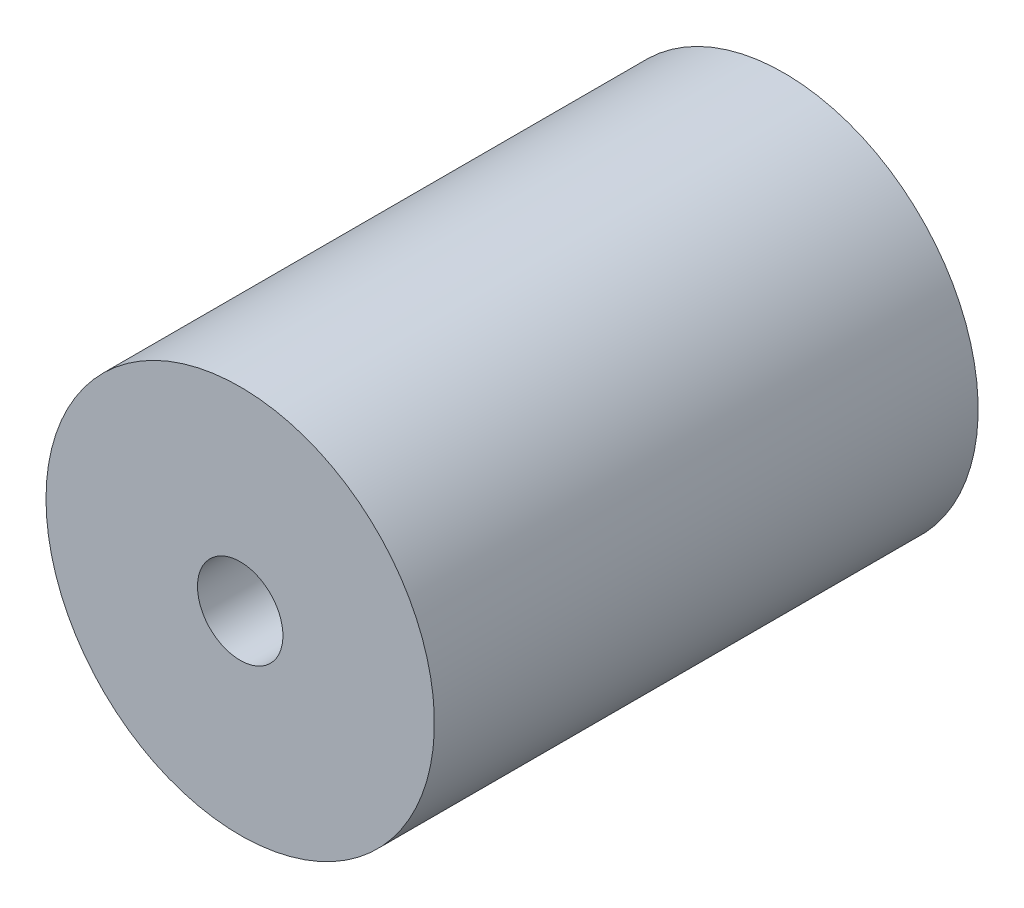
SolidWorks part; units mm, degrees
ref_plane "Plano frontal" through (0, 0, 0) normal (0, 0, 1) x (1, 0, 0)
ref_plane "Plano superior" through (0, 0, 0) normal (0, 1, 0) x (1, 0, 0)
ref_plane "Plano direito" through (0, 0, 0) normal (1, 0, 0) x (0, 0, -1)
sketch "Esboço1" plane through (0, 0, 0) normal (0, 0, 1) x (1, 0, 0)
  circle A0 centre (0, 0) radius 7.5
  circle A1 centre (0, 0) radius 1.65
  dimension "D1" = 3.3
  dimension "D2" = 15
extrude "Ressalto-extrusão1" add sketch "Esboço1" along normal blind 21
